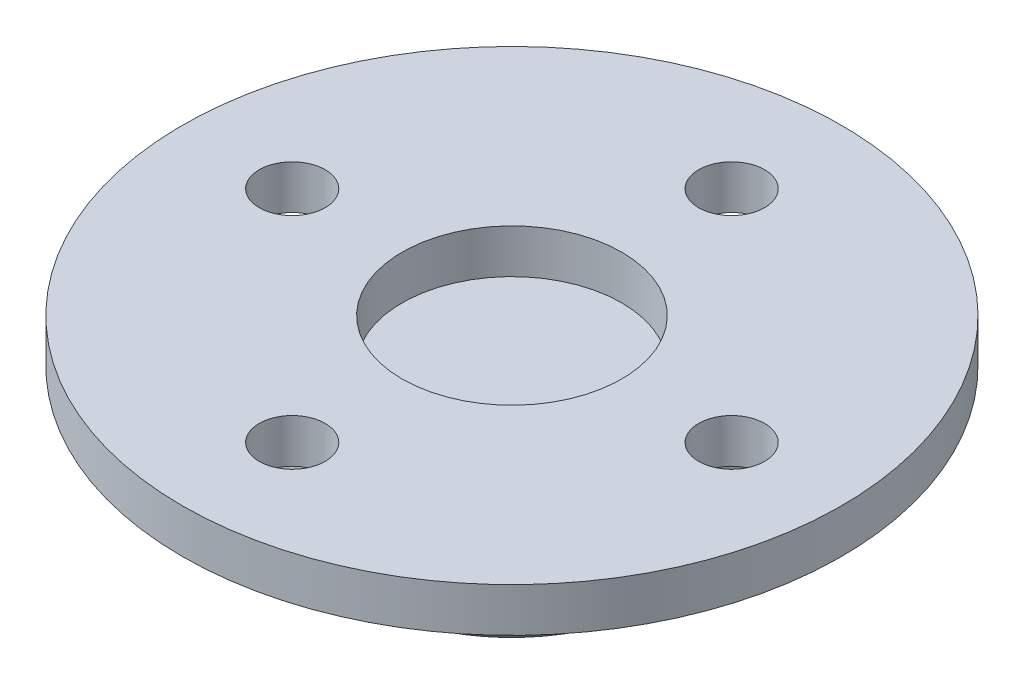
SolidWorks part; units mm, degrees
ref_plane "Front Plane" through (0, 0, 0) normal (0, 0, 1) x (1, 0, 0)
ref_plane "Top Plane" through (0, 0, 0) normal (0, 1, 0) x (1, 0, 0)
ref_plane "Right Plane" through (0, 0, 0) normal (1, 0, 0) x (0, 0, -1)
sketch "Sketch2" plane through (0, 0, 0) normal (0, 1, 0) x (1, 0, 0)
  circle A0 centre (0, 0) radius 19.05
  circle A1 centre (0, 0) radius 6.35
  circle A2 centre (0, 0) radius 12.7 construction
  circle A3 centre (0, 12.7) radius 1.905
  circle A4 centre (12.7, 0) radius 1.905
  circle A5 centre (0, -12.7) radius 1.905
  circle A6 centre (-12.7, 0) radius 1.905
  point P16 (0, 0)
  dimension "D1" = 38.1
  dimension "D2" = 12.7
  dimension "D3" = 25.4
  dimension "D4" = 3.81
  dimension "D5" = 4
extrude "Boss-Extrude1" add sketch "Sketch2" against normal blind 2.54
sketch "Sketch3" plane through (0, -2.54, 0) normal (0, -1, 0) x (1, 0, 0)
  circle A0 centre (0, 0) radius 10.16
  dimension "D1" = 20.32
extrude "Boss-Extrude2" add sketch "Sketch3" along normal blind 7.62
fillet "Fillet1" radius 2.54 1 edges at (0, -10.16, -10.16)
sketch "Sketch5" plane through (0, -10.16, 0) normal (0, -1, 0) x (1, 0, 0)
  line L0 (0, -11.766) -> (0, 11.6045) construction
  line L1 (0, 6.35) -> (0, -6.35)
  arc A2 (0, -6.35) -> (0, 6.35) centre (0, 0) ccw
revolve "Revolve1" add sketch "Sketch5" angle 360 about L0
combine bodies "Combine1" operation type subtract main body 102 bodies to subtract 105
